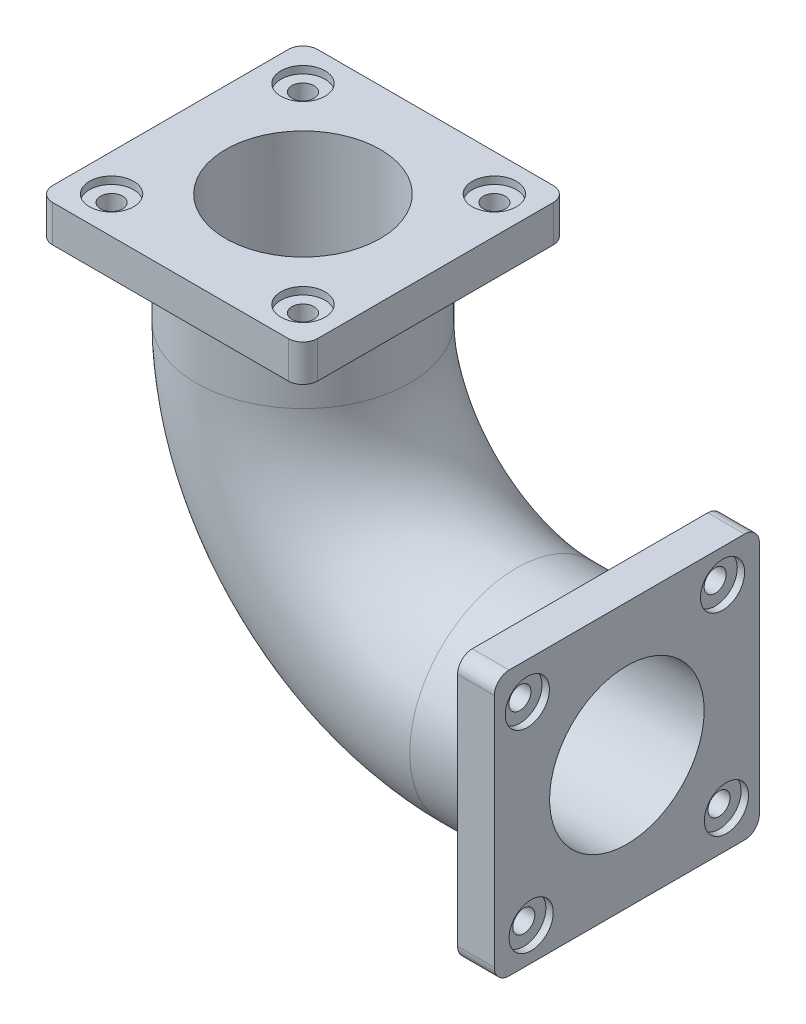
SolidWorks part; units mm, degrees
ref_plane "Front Plane" through (0, 0, 0) normal (0, 0, 1) x (1, 0, 0)
ref_plane "Top Plane" through (0, 0, 0) normal (0, 1, 0) x (1, 0, 0)
ref_plane "Right Plane" through (0, 0, 0) normal (1, 0, 0) x (0, 0, -1)
sketch "Sketch1" plane through (0, 0, 0) normal (0, 0, 1) x (1, 0, 0)
  line L0 (0, 0) -> (-150, 0)
  line L1 (-440, 290) -> (-440, 440)
  arc A0 (-150, 0) -> (-440, 290) centre (-150, 290) cw
  dimension "D1" = 150
  dimension "D3" = 290
  dimension "D2" = 150
sketch "Sketch2" plane through (0, 0, 0) normal (1, 0, 0) x (0, 0, -1)
  circle A0 centre (0, 0) radius 145
  dimension "D1" = 290
sweep "Sweep-Thin1" add profiles "Sketch2" path "Sketch1" parameters "D1"=40
sketch "Sketch3" plane through (0, 0, 0) normal (1, 0, 0) x (0, 0, -1)
  line L1 (180, -180) -> (-180, -180)
  line L2 (180, -180) -> (180, 180)
  line L3 (180, 180) -> (-180, 180)
  line L4 (-180, -180) -> (-180, 180)
  line L5 (180, -180) -> (-180, 180) construction
  line L6 (180, 180) -> (-180, -180) construction
  point P0 (0, 0)
  circle M2 centre (0, 0) radius 145
  dimension "D1" = 360
  dimension "D2" = 360
extrude "Boss-Extrude1" add sketch "Sketch3" against normal blind 50 contours L4 L1 L2 L3 M2
fillet "Fillet1" radius 20 4 edges at (-25, -180, 180) (-25, -180, -180) (-25, 180, -180) (-25, 180, 180)
sketch "Sketch4" plane through (0, 440, 0) normal (0, 1, 0) x (1, 0, 0)
  line L0 (-440, 0) -> (-150, 0) construction
  line L1 (-260, -180) -> (-620, -180)
  line L2 (-260, -180) -> (-260, 180)
  line L3 (-260, 180) -> (-620, 180)
  line L4 (-620, -180) -> (-620, 180)
  line L5 (-260, -180) -> (-620, 180) construction
  line L6 (-260, 180) -> (-620, -180) construction
  point P0 (-440, 0)
  circle M6 centre (-440, 0) radius 145
  dimension "D1" = 360
  dimension "D2" = 360
extrude "Boss-Extrude2" add sketch "Sketch4" against normal blind 50 contours L4 L1 L2 L3 M6
fillet "Fillet2" radius 20 4 edges at (-620, 415, 180) (-260, 415, -180) (-620, 415, -180) (-260, 415, 180)
sketch "Sketch6" plane through (0, 0, 0) normal (1, 0, 0) x (0, 0, -1)
  line L1 (-130, -130) -> (130, -130) construction
  line L2 (-130, -130) -> (-130, 130) construction
  line L3 (-130, 130) -> (130, 130) construction
  line L4 (130, -130) -> (130, 130) construction
  line L5 (-130, -130) -> (130, 130) construction
  line L6 (-130, 130) -> (130, -130) construction
  circle A0 centre (-135.2396, 130) radius 30
  point P0 (0, 0)
  dimension "D3" = 60
  dimension "D1" = 260
  dimension "D2" = 260
extrude "Cut-Extrude1" cut sketch "Sketch6" against normal blind 10 contours L3 A0 L2 | L2 A0 L3
sketch "Sketch7" plane through (-10, 0, 0) normal (1, 0, 0) x (0, 0, -1)
sketch "Sketch8" plane through (-10, 0, 0) normal (1, 0, 0) x (0, 0, -1)
  circle A0 centre (-135.2396, 130) radius 15
  dimension "D1" = 30
extrude "Cut-Extrude2" cut sketch "Sketch8" against normal up to next
pattern_circular "CirPattern1" count 4 over 360 about axis through (0, 0, 0) along (1, 0, 0) of "Cut-Extrude2", "Cut-Extrude1"
sketch "Sketch10" plane through (0, 440, 0) normal (0, 1, 0) x (1, 0, 0)
  line L1 (-570, -130) -> (-310, -130) construction
  line L2 (-570, -130) -> (-570, 130) construction
  line L3 (-570, 130) -> (-310, 130) construction
  line L4 (-310, -130) -> (-310, 130) construction
  line L5 (-570, -130) -> (-310, 130) construction
  line L6 (-570, 130) -> (-310, -130) construction
  circle A0 centre (-570, 130) radius 30
  point P0 (-440, 0)
  dimension "D3" = 60
  dimension "D1" = 260
  dimension "D2" = 260
extrude "Cut-Extrude3" cut sketch "Sketch10" against normal blind 10
sketch "Sketch11" plane through (0, 430, 0) normal (0, 1, 0) x (1, 0, 0)
  circle A0 centre (-570, 130) radius 15
  dimension "D1" = 30
extrude "Cut-Extrude4" cut sketch "Sketch11" against normal up to next
pattern_circular "CirPattern3" count 4 over 360 about axis through (-440, 0, 0) along (0, 1, 0) of "Cut-Extrude4", "Cut-Extrude3"
